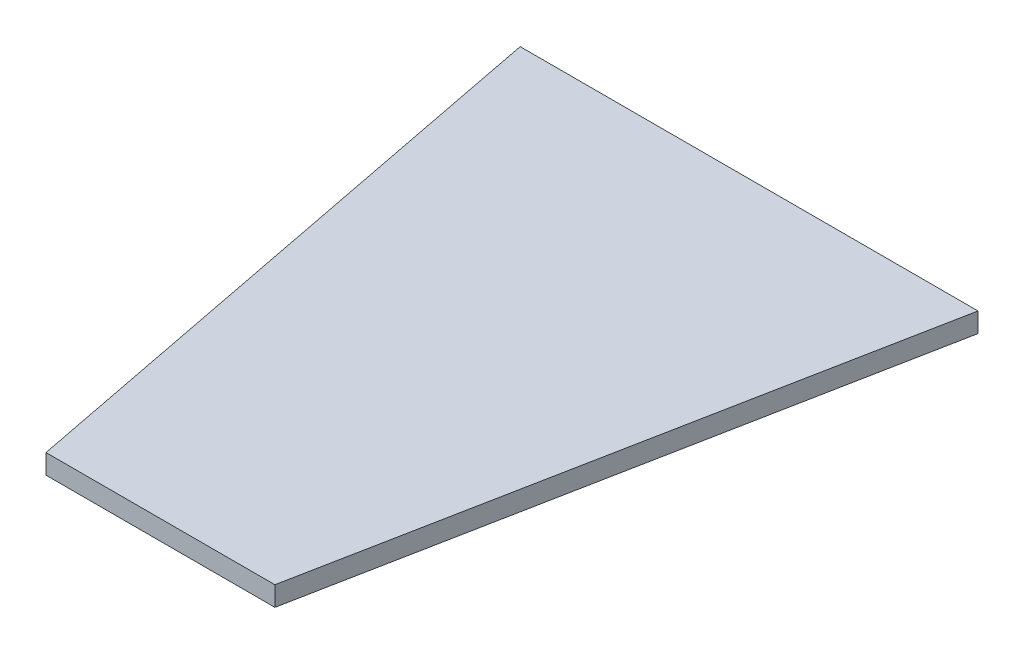
SolidWorks part; units mm, degrees
ref_plane "Front" through (0, 0, 0) normal (0, 0, 1) x (1, 0, 0)
ref_plane "Top" through (0, 0, 0) normal (0, 1, 0) x (1, 0, 0)
ref_plane "Right" through (0, 0, 0) normal (1, 0, 0) x (0, 0, -1)
sketch "Sketch1" plane through (0, 0, 0) normal (0, 1, 0) x (1, 0, 0)
  line L1 (-31.2366, 18.7231) -> (38.7634, 18.7231)
  line L3 (21.2634, -71.2769) -> (38.7634, 18.7231)
  line L5 (-13.7366, -71.2769) -> (21.2634, -71.2769)
  line L6 (-31.2366, 18.7231) -> (-13.7366, -71.2769)
  dimension "D1" = 70
  dimension "D4" = 35
extrude "Boss-Extrude1" add sketch "Sketch1" along normal blind 3
